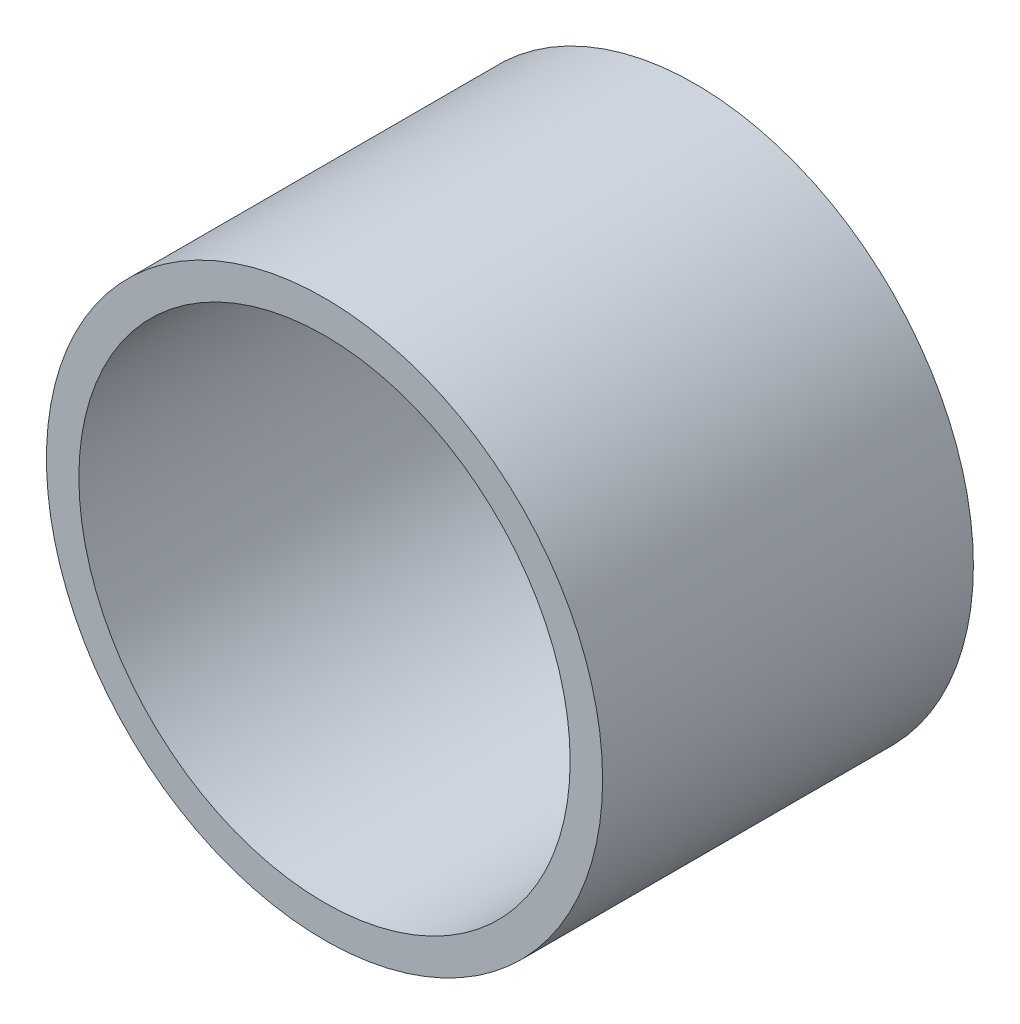
SolidWorks part; units mm, degrees
ref_plane "Alzado" through (0, 0, 0) normal (0, 0, 1) x (1, 0, 0)
ref_plane "Planta" through (0, 0, 0) normal (0, 1, 0) x (1, 0, 0)
ref_plane "Vista lateral" through (0, 0, 0) normal (1, 0, 0) x (0, 0, -1)
sketch "Croquis1" plane through (0, 0, 0) normal (0, 0, 1) x (1, 0, 0)
  circle A0 centre (0, 0) radius 6
extrude "Saliente-Extruir1" add sketch "Croquis1" along normal blind 8
sketch "Croquis2" plane through (0, 0, 0) normal (0, 0, 1) x (1, 0, 0)
  circle A0 centre (0, 0) radius 5.3
extrude "Cortar-Extruir1" cut sketch "Croquis2" along normal blind 8
